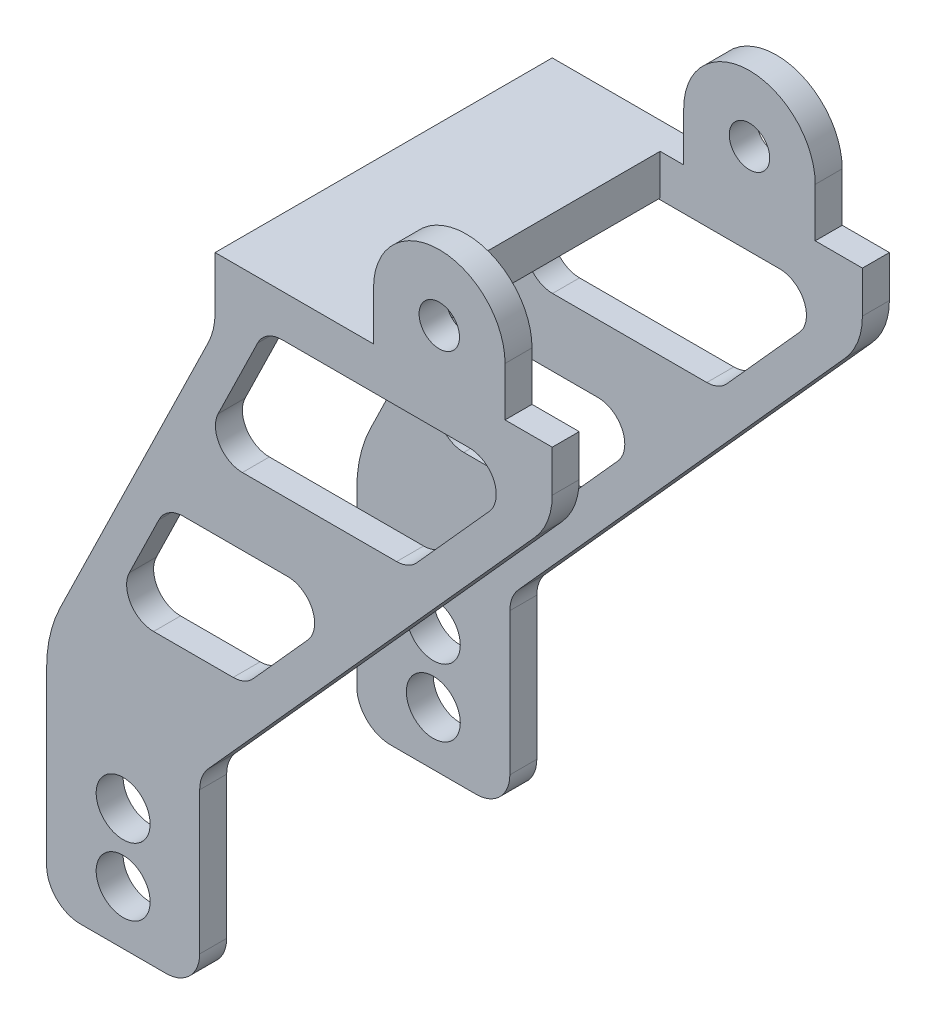
SolidWorks part; units mm, degrees
material "Alumina"
ref_plane "Plano frontal" through (0, 0, 0) normal (0, 0, 1) x (1, 0, 0)
ref_plane "Plano superior" through (0, 0, 0) normal (0, 1, 0) x (1, 0, 0)
ref_plane "Plano direito" through (0, 0, 0) normal (1, 0, 0) x (0, 0, -1)
sketch "Esboço1" plane through (0, 0, 0) normal (0, 0, 1) x (1, 0, 0)
  line L0 (-11.35, 0) -> (11.35, 0)
  line L1 (11.35, 0) -> (11.35, 26.0846)
  line L2 (-11.35, 0) -> (-11.35, 30.3826)
  line L3 (-9.3259, 39.1501) -> (12.6251, 84.1562)
  line L4 (13.6372, 88.5399) -> (13.6372, 96.2313)
  line L5 (13.6372, 96.2313) -> (63.6372, 96.2313)
  line L6 (63.6372, 96.2313) -> (63.6372, 90.062)
  line L7 (12.6297, 29.4252) -> (61.0778, 83.3809)
  arc A0 (-11.35, 30.3826) -> (-9.3259, 39.1501) centre (8.65, 30.3826) cw
  arc A1 (11.35, 26.0846) -> (12.6297, 29.4252) centre (16.35, 26.0846) cw
  arc A2 (63.6372, 90.062) -> (61.0778, 83.3809) centre (53.6372, 90.062) cw
  arc A3 (12.6251, 84.1562) -> (13.6372, 88.5399) centre (3.6372, 88.5399) ccw
  point P11 (-11.35, 35)
  point P14 (11.35, 28)
  point P17 (63.6372, 86.2313)
  point P20 (13.6372, 86.2313)
  dimension "D10" = 20
  dimension "D11" = 5
  dimension "D12" = 10
  dimension "D13" = 10
  dimension "D1" = 22.7
  dimension "D2" = 11.35
  dimension "D3" = 35
  dimension "D4" = 28
  dimension "D5" = 26
  dimension "D6" = 57
  dimension "D7" = 10
  dimension "D8" = 50
  dimension "D9" = 10
extrude "Ressalto-extrusão1" add sketch "Esboço1" along normal mid plane 4
fillet "Filete1" radius 5 2 edges at (-11.35, 0, 0) (11.35, 0, 0)
sketch "Esboço2" plane through (0, 0, 2) normal (0, 0, 1) x (1, 0, 0)
  line L0 (-6.35, 0) -> (6.35, 0) construction
  circle A0 centre (0, 8) radius 4
  circle A1 centre (0, 18) radius 4
  dimension "D1" = 8
  dimension "D2" = 8
  dimension "D3" = 10
  dimension "D4" = 8
extrude "Corte-extrusão1" cut sketch "Esboço2" against normal through all
sketch "Esboço3" plane through (0, 0, 2) normal (0, 0, 1) x (1, 0, 0)
  line L0 (4.5162, 43) -> (16.3148, 43)
  line L1 (19.291, 44.3276) -> (27.3723, 53.3276)
  line L2 (51.3337, 90) -> (23.5378, 90)
  line L3 (19.9426, 87.7535) -> (14.0898, 75.7535)
  line L4 (8.9058, 60) -> (24.3961, 60)
  line L5 (17.685, 70) -> (40.5587, 70)
  line L6 (43.5349, 71.3276) -> (54.31, 83.3276)
  line L7 (5.3106, 57.7535) -> (0.921, 48.7535)
  line L8 (-6.35, 0) -> (6.35, 0) construction
  line L10 (12.6297, 29.4252) -> (61.0778, 83.3809) construction
  line L11 (12.6251, 84.1562) -> (-9.3259, 39.1501) construction
  arc A2 (16.3148, 43) -> (19.291, 44.3276) centre (16.3148, 47) ccw
  arc A3 (0.921, 48.7535) -> (4.5162, 43) centre (4.5162, 47) ccw
  arc A4 (8.9058, 60) -> (5.3106, 57.7535) centre (8.9058, 56) ccw
  arc A5 (24.3961, 60) -> (27.3723, 53.3276) centre (24.3961, 56) cw
  arc A6 (40.5587, 70) -> (43.5349, 71.3276) centre (40.5587, 74) ccw
  arc A7 (17.685, 70) -> (14.0898, 75.7535) centre (17.685, 74) cw
  arc A8 (23.5378, 90) -> (19.9426, 87.7535) centre (23.5378, 86) ccw
  arc A9 (54.31, 83.3276) -> (51.3337, 90) centre (51.3337, 86) ccw
  point P24 (42.3429, 70)
  dimension "D4" = 5
  dimension "D7" = 4
  dimension "D1" = 43
  dimension "D2" = 17
  dimension "D3" = 5
  dimension "D5" = 10
  dimension "D6" = 20
extrude "Corte-extrusão2" cut sketch "Esboço3" against normal through all
sketch "Esboço4" plane through (0, 0, 2) normal (0, 0, 1) x (1, 0, 0)
  line L0 (37.1372, 96.2313) -> (37.1372, 103.4813)
  line L1 (63.6372, 96.2313) -> (13.6372, 96.2313) construction
  line L2 (56.6372, 103.4813) -> (56.6372, 96.2313)
  line L3 (56.6372, 96.2313) -> (37.1372, 96.2313)
  line L4 (63.6372, 90.062) -> (63.6372, 96.2313) construction
  arc A0 (37.1372, 103.4813) -> (56.6372, 103.4813) centre (46.8872, 103.4813) cw
  dimension "D1" = 7
  dimension "D2" = 17
  dimension "D3" = 9.75
extrude "Ressalto-extrusão2" add sketch "Esboço4" against normal up to surface (4 mm away) up to face at (13.4272, 51.2912, -2)
sketch "Esboço5" plane through (0, 0, 2) normal (0, 0, 1) x (1, 0, 0)
  circle A0 centre (46.8872, 103.4813) radius 3
  dimension "D1" = 6
extrude "Corte-extrusão3" cut sketch "Esboço5" against normal through all
sketch "Esboço6" plane through (0, 0, 2) normal (0, 0, 1) x (1, 0, 0)
  line L1 (13.6372, 96.2313) -> (33.6372, 96.2313)
  line L2 (13.6372, 96.2313) -> (13.6372, 90.2313)
  line L3 (13.6372, 90.2313) -> (33.6372, 90.2313)
  line L4 (33.6372, 96.2313) -> (33.6372, 90.2313)
  dimension "D1" = 20
  dimension "D2" = 6
extrude "Ressalto-extrusão3" add sketch "Esboço6" against normal blind 25
mirror "Espelhar5" about plane through (0, 0, -23) normal (0, 0, 1) of bodies 106
